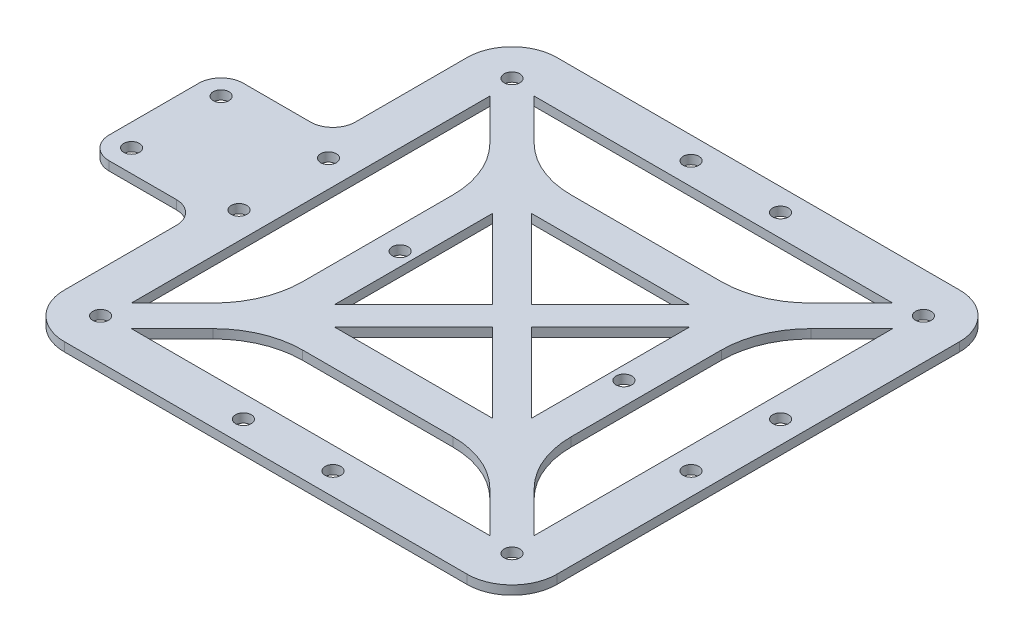
SolidWorks part; units mm, degrees
ref_plane "前视基准面" through (0, 0, 0) normal (0, 0, 1) x (1, 0, 0)
ref_plane "上视基准面" through (0, 0, 0) normal (0, 1, 0) x (1, 0, 0)
ref_plane "右视基准面" through (0, 0, 0) normal (1, 0, 0) x (0, 0, -1)
sketch "草图1" plane through (0, 0, 0) normal (0, 1, 0) x (1, 0, 0)
  line L1 (45, -55) -> (-45, -55)
  line L2 (55, -45) -> (55, 45)
  line L3 (45, 55) -> (21.0439, 55)
  line L4 (-55, -45) -> (-55, -19.9898)
  line L5 (55, -55) -> (-55, 55) construction
  line L6 (55, 55) -> (-55, -55) construction
  line L23 (-17.6777, 22) -> (0, 4.3223)
  line L24 (17.6777, 22) -> (0, 4.3223)
  line L25 (-17.6777, 22) -> (17.6777, 22)
  line L26 (22, 17.6777) -> (4.3223, 0)
  line L27 (22, -17.6777) -> (4.3223, 0)
  line L28 (22, 17.6777) -> (22, -17.6777)
  line L29 (17.6777, -22) -> (0, -4.3223)
  line L30 (-17.6777, -22) -> (0, -4.3223)
  line L31 (17.6777, -22) -> (-17.6777, -22)
  line L32 (-22, -17.6777) -> (-4.3223, 0)
  line L33 (-22, 17.6777) -> (-4.3223, 0)
  line L34 (-22, -17.6777) -> (-22, 17.6777)
  line L35 (0, 0) -> (0, 4.3223) construction
  line L43 (0, 0) -> (-22, 0) construction
  line L44 (0, 0) -> (0, -55) construction
  line L52 (18.8439, 55) -> (1.0439, 55)
  line L53 (-1.1561, 55) -> (-45, 55)
  line L54 (-1.1561, 55) -> (21.0439, 55)
  line L55 (-30.9081, 35.8579) -> (-40.0503, 45)
  line L56 (-40.0503, 45) -> (40.0503, 45)
  line L57 (30.9081, 35.8579) -> (40.0503, 45)
  line L58 (-16.766, 30) -> (16.766, 30)
  line L59 (35.8579, -30.9081) -> (45, -40.0503)
  line L60 (45, 40.0503) -> (45, -40.0503)
  line L61 (35.8579, 30.9081) -> (45, 40.0503)
  line L62 (30, 16.766) -> (30, -16.766)
  line L63 (-30.9081, -35.8579) -> (-40.0503, -45)
  line L64 (40.0503, -45) -> (-40.0503, -45)
  line L65 (30.9081, -35.8579) -> (40.0503, -45)
  line L66 (16.766, -30) -> (-16.766, -30)
  line L67 (-35.8579, 30.9081) -> (-45, 40.0503)
  line L68 (-45, -40.0503) -> (-45, 40.0503)
  line L69 (-35.8579, -30.9081) -> (-45, -40.0503)
  line L70 (-30, -16.766) -> (-30, 16.766)
  line L72 (-60.0026, -14.9898) -> (-74.9974, -14.9974)
  line L73 (-60.0026, 14.9898) -> (-74.9974, 14.9974)
  line L74 (-80, -9.9974) -> (-80, 9.9974)
  line L75 (-55, 19.9898) -> (-55, 45)
  circle A0 centre (-45.9619, 45.9619) radius 1.75
  arc A1 (45, -55) -> (55, -45) centre (45, -45) ccw
  arc A2 (-45, -55) -> (-55, -45) centre (-45, -45) cw
  arc A3 (55, 45) -> (45, 55) centre (45, 45) ccw
  arc A4 (-45, 55) -> (-55, 45) centre (-45, 45) ccw
  circle A5 centre (45.9619, 45.9619) radius 1.75
  circle A14 centre (-75, -10) radius 1.75
  circle A15 centre (-75, 10) radius 1.75
  circle A44 centre (-45.9619, -45.9619) radius 1.75 [skipped]
  circle A45 centre (45.9619, -45.9619) radius 1.75 [skipped]
  circle A46 centre (-45.9619, -45.9619) radius 1.75
  circle A47 centre (45.9619, -45.9619) radius 1.75
  arc A48 (16.766, 30) -> (30.9081, 35.8579) centre (16.766, 50) ccw
  arc A49 (-16.766, 30) -> (-30.9081, 35.8579) centre (-16.766, 50) cw
  arc A50 (30, -16.766) -> (35.8579, -30.9081) centre (50, -16.766) ccw
  arc A51 (30, 16.766) -> (35.8579, 30.9081) centre (50, 16.766) cw
  arc A52 (-16.766, -30) -> (-30.9081, -35.8579) centre (-16.766, -50) ccw
  arc A53 (16.766, -30) -> (30.9081, -35.8579) centre (16.766, -50) cw
  arc A54 (-30, 16.766) -> (-35.8579, 30.9081) centre (-50, 16.766) ccw
  arc A55 (-30, -16.766) -> (-35.8579, -30.9081) centre (-50, -16.766) cw
  circle A56 centre (-51, 10) radius 1.75
  circle A57 centre (-51, -10) radius 1.75
  arc A58 (-60.0026, -14.9898) -> (-55, -19.9898) centre (-60, -19.9898) cw
  arc A59 (-55, 19.9898) -> (-60.0026, 14.9898) centre (-60, 19.9898) cw
  arc A60 (-74.9974, -14.9974) -> (-80, -9.9974) centre (-75, -9.9974) cw
  arc A61 (-74.9974, 14.9974) -> (-80, 9.9974) centre (-75, 9.9974) ccw
  circle A62 centre (-10, 50) radius 1.75
  circle A63 centre (10, 50) radius 1.75
  circle A64 centre (50, -10) radius 1.75
  circle A65 centre (50, 10) radius 1.75
  circle A66 centre (-10, -50) radius 1.75
  circle A67 centre (10, -50) radius 1.75
  circle A70 centre (-50, 10) radius 1.75 [skipped]
  circle A71 centre (-50, -10) radius 1.75 [skipped]
  circle A72 centre (-25, 0) radius 1.75
  circle A73 centre (25, 0) radius 1.75
  point P0 (0, 0)
  point P45 (0, 0)
  point P58 (0, 0)
  point P76 (0, 0)
  point P91 (0, 0)
  point P92 (-80, 0)
  point P101 (-25, 0)
  point P112 (-55, 14.9872)
  point P115 (-80, -15)
  point P118 (-80, 15)
  point P124 (-3.6834, -3.6834)
  point P130 (0, 0)
  dimension "D3" = 3.5
  dimension "D5" = 10
  dimension "D13" = 20
  dimension "D14" = 65
  dimension "D16" = 45
  dimension "D17" = 45
  dimension "D22" = 20
  dimension "D23" = 25
  dimension "D6" = 20
  dimension "D25" = 3.5
  dimension "D27" = 3.5
  dimension "D28" = 5
  dimension "D19" = 3.5
  dimension "D29" = 4
  dimension "D30" = 3.5
  dimension "D1" = 110
  dimension "D2" = 110
  dimension "D4" = 65
  dimension "D7" = 4
  dimension "D8" = 45
  dimension "D9" = 7
  dimension "D11" = 22
  dimension "D15" = 20
  dimension "D18" = 22
  dimension "D20" = 30
  dimension "D24" = 30
  dimension "D21" = 5
  dimension "D26" = 24
  dimension "D31" = 25
  dimension "D32" = 25
  dimension "D10" = 4
  dimension "D12" = 4
extrude "凸台-拉伸1" add sketch "草图1" along normal blind 2
